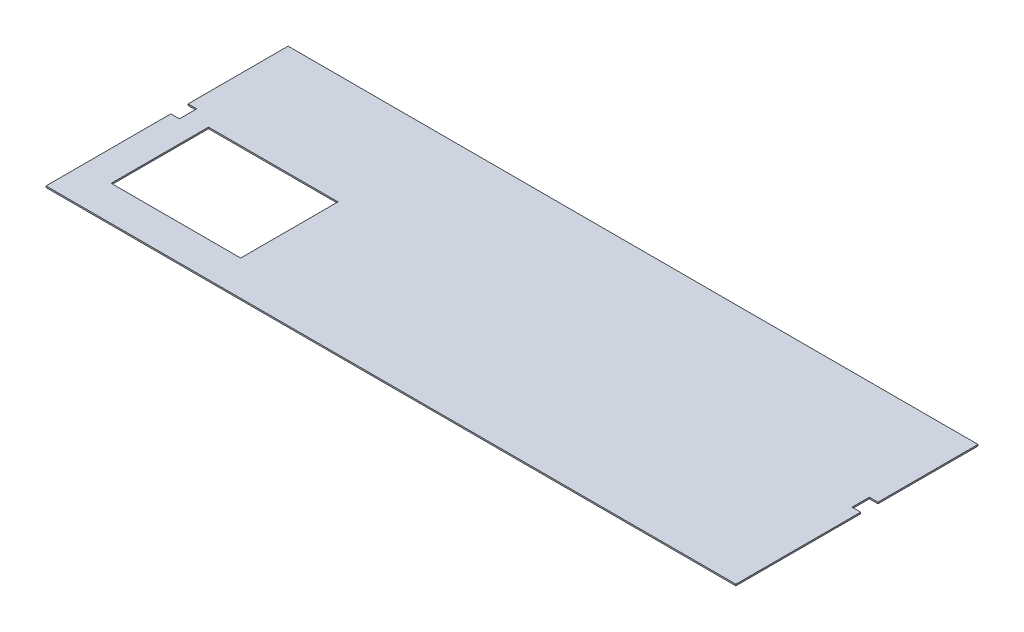
SolidWorks part; units mm, degrees
material "MDF"
ref_plane "Front Plane" through (0, 0, 0) normal (0, 0, 1) x (1, 0, 0)
ref_plane "Top Plane" through (0, 0, 0) normal (0, 1, 0) x (1, 0, 0)
ref_plane "Right Plane" through (0, 0, 0) normal (1, 0, 0) x (0, 0, -1)
sketch "Sketch1" plane through (0, 0, 0) normal (0, 1, 0) x (1, 0, 0)
  line L0 (-762, 46.42) -> (-742.95, 46.42)
  line L5 (-762, -267.42) -> (762, -267.42)
  line L6 (-762, -267.42) -> (-762, 8.32)
  line L7 (-762, 267.42) -> (762, 267.42)
  line L8 (762, -267.42) -> (762, 8.32)
  line L9 (-762, -267.42) -> (762, 267.42) construction
  line L10 (-762, 267.42) -> (762, -267.42) construction
  line L11 (-742.95, 46.42) -> (-742.95, 8.32)
  line L12 (-742.95, 8.32) -> (-762, 8.32)
  line L13 (-762, 46.42) -> (-762, 267.42)
  line L14 (0, 526.1693) -> (0, -526.1693) construction
  line L15 (742.95, 8.32) -> (762, 8.32)
  line L16 (742.95, 46.42) -> (742.95, 8.32)
  line L17 (762, 46.42) -> (742.95, 46.42)
  line L18 (762, 46.42) -> (762, 267.42)
  point P0 (0, 0)
  point P14 (0, 0)
  dimension "D1" = 275.74
  dimension "D2" = 38.1
  dimension "D3" = 221
  dimension "D4" = 19.05
  dimension "D5" = 1524
extrude "Boss-Extrude1" add sketch "Sketch1" along normal blind 3.175
sketch "Sketch2" plane through (0, 3.175, 0) normal (0, 1, 0) x (1, 0, 0)
  line L1 (-695, -190.42) -> (-409, -190.42)
  line L2 (-695, -190.42) -> (-695, 24.58)
  line L3 (-695, 24.58) -> (-409, 24.58)
  line L4 (-409, -190.42) -> (-409, 24.58)
  dimension "D1" = 67
  dimension "D2" = 77
  dimension "D3" = 286
  dimension "D4" = 215
extrude "Cut-Extrude1" cut sketch "Sketch2" against normal up to next
